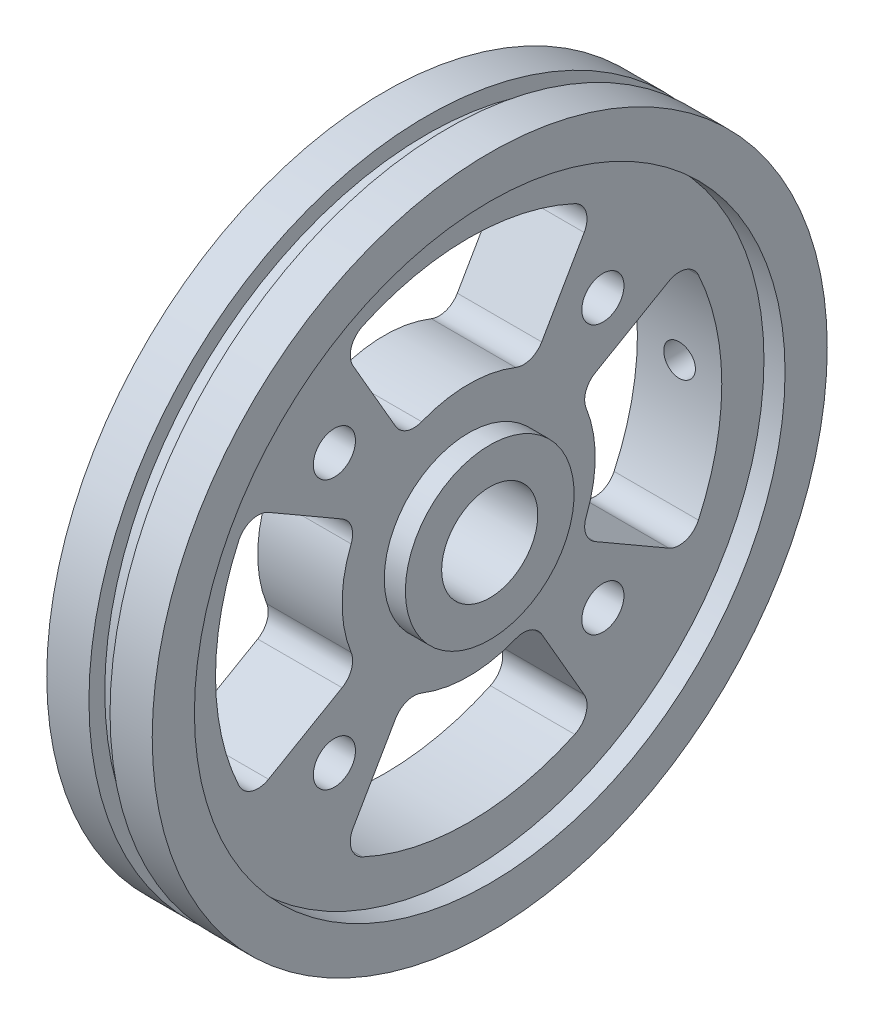
SolidWorks part; units mm, degrees
ref_plane "Front Plane" through (0, 0, 0) normal (0, 0, 1) x (1, 0, 0)
ref_plane "Top Plane" through (0, 0, 0) normal (0, 1, 0) x (1, 0, 0)
ref_plane "Right Plane" through (0, 0, 0) normal (1, 0, 0) x (0, 0, -1)
sketch "Sketch1" plane through (0, 0, 0) normal (0, 1, 0) x (1, 0, 0)
  line L0 (0, 0) -> (0, 17.528) construction
  line L1 (0, 0) -> (17.08, 0) construction
  line L2 (0, 2.28) -> (0, 16)
  line L3 (0, 16) -> (5, 16)
  line L4 (5, 16) -> (5, 14)
  line L5 (5, 14) -> (4, 14)
  line L6 (4, 14) -> (4, 4)
  line L7 (4, 4) -> (5, 4)
  line L8 (5, 4) -> (5, 2.28)
  line L9 (5, 2.28) -> (0, 2.28)
  dimension "D1" = 5
  dimension "D2" = 5
  dimension "D3" = 4
  dimension "D4" = 8
  dimension "D5" = 4.56
  dimension "D6" = 28
  dimension "D7" = 32
revolve "Revolve1" add sketch "Sketch1" angle 360 about L1
sketch "Sketch2" plane through (0, 0, 0) normal (0, 1, 0) x (1, 0, 0)
  line L0 (0, 0) -> (15.5342, 0) construction
  line L1 (0, 16) -> (0, -16) construction
  line L2 (2, 0) -> (2, 16)
  line L3 (2, 16) -> (2.75, 16)
  line L4 (2.75, 16) -> (2.75, 11.5)
  line L5 (2.75, 11.5) -> (2.4, 11.5)
  line L6 (2.4, 11.5) -> (2.4, 0)
  line L7 (2.4, 0) -> (2, 0)
  line L8 (0, 0) -> (0, 20.8012) construction
  line L9 (2, 0) -> (2, 27.2877) construction
  line L10 (5, 16) -> (0, 16) construction
  dimension "D1" = 4.5
  dimension "D2" = 2
  dimension "D3" = 1.5
  dimension "D4" = 0.8
revolve "Cut-Revolve1" cut sketch "Sketch2" angle 360 about L9
sketch "Sketch3" plane through (4, 0, 0) normal (1, 0, 0) x (0, 0, -1)
  line L2 (0, 0) -> (13.3792, 0) construction
  line L3 (0, 0) -> (10.3923, 6) construction
  line L4 (0, 0) -> (10.3923, -6) construction
  line L5 (5.1962, 3) -> (10.3923, 6)
  line L6 (5.1962, -3) -> (10.3923, -6)
  arc A4 (10.3923, 6) -> (10.3923, -6) centre (0, 0) cw
  arc A5 (5.1962, 3) -> (5.1962, -3) centre (0, 0) cw
  circle A6 centre (0, 0) radius 2.28 construction
  dimension "D1" = 6
  dimension "D2" = 12
  dimension "D3" = 12
extrude "Cut-Extrude1" cut sketch "Sketch3" against normal through all
fillet "Fillet1" radius 1 4 edges at (2, -6, -10.3923) (2, -3, -5.1962) (2, 3, -5.1962) (2, 6, -10.3923)
ref_axis "Axis1" through (0, 0, 0) along (1, 0, 0)
pattern_circular "CirPattern1" count 4 over 360 about axis through (0, 0, 0) along (1, 0, 0) of "Cut-Extrude1", "Fillet1"
sketch "Sketch4" plane through (0, 0, 0) normal (0, 1, 0) x (1, 0, 0)
  line L0 (5, 16) -> (2.75, 16) construction
  line L1 (3, 15.25) -> (2, 15.25)
  line L2 (3, 15.25) -> (3, 16)
  line L3 (3, 16) -> (2, 16)
  line L4 (2, 15.25) -> (2, 16)
  line L5 (3, 15.25) -> (2, 16) construction
  line L6 (3, 16) -> (2, 15.25) construction
  line L7 (5, -16) -> (5, 16) construction
  point P0 (2.5, 15.625)
  dimension "D1" = 0.75
  dimension "D2" = 1
  dimension "D3" = 2
revolve "Cut-Revolve2" cut sketch "Sketch4" angle 360 about axis through (0, 0, 0) along (1, 0, 0)
sketch "Sketch6" [suppressed] plane through (0, 0, 0) normal (1, 0, 0) x (0, 0, -1)
  line L0 (16, 0) -> (12.6141, 0) construction
  line L2 (15.5, 0.5) -> (16, 0.5)
  line L3 (15.5, 0.5) -> (15.5, -0.5)
  line L4 (15.5, -0.5) -> (16, -0.5)
  line L5 (16, 0.5) -> (16, -0.5)
  line L6 (15.5, 0.5) -> (16, -0.5) construction
  line L7 (15.5, -0.5) -> (16, 0.5) construction
  circle A0 centre (0, 0) radius 16 construction
  point P6 (15.75, 0)
  dimension "D1" = 0.5
  dimension "D2" = 1
extrude "Cut-Extrude3" [suppressed] cut sketch "Sketch6" along normal through all
pattern_linear "LPattern1" [suppressed] count 2 spacing 2
pattern_circular "CirPattern2" [suppressed] count 30 over 360
sketch "Sketch9" plane through (0, 0, 0) normal (-1, 0, 0) x (0, 0, 1)
  line L0 (6.364, 6.364) -> (4.3467, 7.5286) construction
  line L1 (5.4772, 9.4868) -> (3.4641, 6) construction
  line L2 (6.364, 6.364) -> (7.5286, 4.3467) construction
  line L3 (6, 3.4641) -> (9.4868, 5.4772) construction
  circle A0 centre (6.364, 6.364) radius 1
  dimension "D1" = 2
  dimension "D2" = 9
extrude "Cut-Extrude4" cut sketch "Sketch9" against normal through all
pattern_circular "CirPattern3" count 4 over 360 about axis through (0, 0, 0) along (1, 0, 0) of "Cut-Extrude4"
